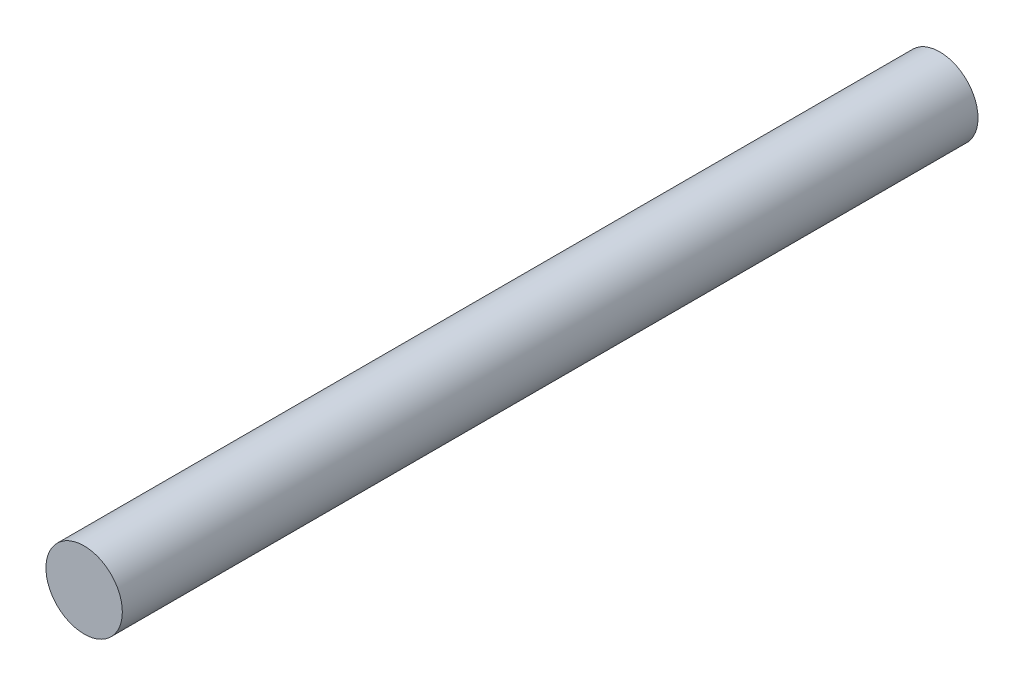
SolidWorks part; units mm, degrees
ref_plane "Front Plane" through (0, 0, 0) normal (0, 0, 1) x (1, 0, 0)
ref_plane "Top Plane" through (0, 0, 0) normal (0, 1, 0) x (1, 0, 0)
ref_plane "Right Plane" through (0, 0, 0) normal (1, 0, 0) x (0, 0, -1)
sketch "Sketch1" plane through (0, 0, 0) normal (0, 0, 1) x (1, 0, 0)
  circle A0 centre (0, 0) radius 1.9844
  dimension "D1" = 3.9688
extrude "Boss-Extrude1" add sketch "Sketch1" along normal blind 44.45
